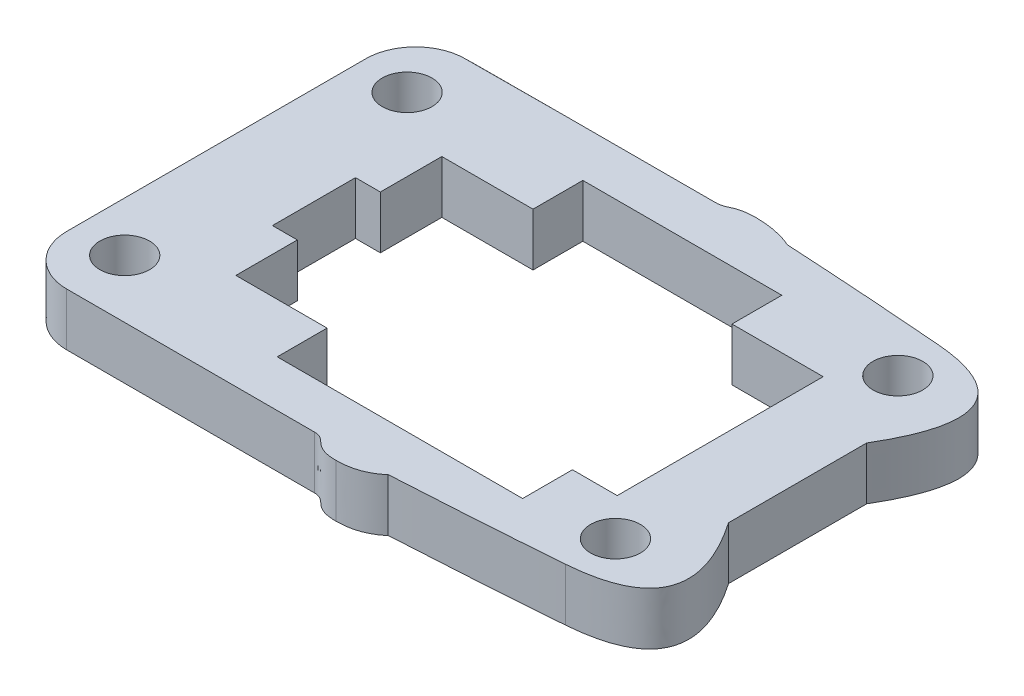
SolidWorks part; units mm, degrees
ref_plane "Front Plane" through (0, 0, 0) normal (0, 0, 1) x (1, 0, 0)
ref_plane "Top Plane" through (0, 0, 0) normal (0, 1, 0) x (1, 0, 0)
ref_plane "Right Plane" through (0, 0, 0) normal (1, 0, 0) x (0, 0, -1)
sketch "Sketch1" plane through (0, 0, 0) normal (0, 1, 0) x (1, 0, 0)
  line L0 (-5.1419, -4.4237) -> (-5.1419, -23.5635) construction
  line L1 (24.4058, -21.4242) -> (-7.2594, -21.4242) construction
  line L25 (-8.1366, -21.9243) -> (-8.1366, -3.9237)
  line L26 (26.9756, -8.8678) -> (26.9756, -17.1873)
  line L27 (-2.247, -15.4242) -> (-0.7496, -15.4242)
  line L28 (-0.7496, -15.4242) -> (-0.7496, -19.1243)
  line L29 (-0.7496, -19.1243) -> (4.7404, -19.1243)
  line L30 (4.7404, -19.1243) -> (4.7404, -22.1242)
  line L31 (4.7404, -22.1242) -> (19.5144, -22.1242)
  line L32 (19.5144, -22.1242) -> (19.5144, -19.1243)
  line L33 (19.5144, -19.1243) -> (22.2095, -19.1243)
  line L34 (22.2095, -19.1243) -> (22.2095, -6.7239)
  line L35 (22.2095, -6.7239) -> (16.7193, -6.7239)
  line L36 (16.7193, -6.7239) -> (16.7193, -3.7237)
  line L37 (16.7193, -3.7237) -> (4.7404, -3.7237)
  line L38 (4.7404, -3.7237) -> (4.7404, -6.7239)
  line L39 (4.7404, -6.7239) -> (-0.7496, -6.7239)
  line L40 (-0.7496, -6.7239) -> (-0.7496, -10.424)
  line L41 (-0.7496, -10.424) -> (-2.247, -10.424)
  line L42 (-2.247, -10.424) -> (-2.247, -15.4242)
  circle A0 centre (-5.1419, -4.4237) radius 1.4974
  circle A1 centre (24.4058, -4.4237) radius 1.4974
  circle A2 centre (-5.1419, -21.4242) radius 1.4974
  circle A3 centre (24.4058, -21.4242) radius 1.4974
  spline S9 degree 3 poles (-8.1366, -3.9237) (-8.1366, -3.1281) (-7.821, -2.365) (-7.2594, -1.8022) knots 1 1 1 1 2 2 2 2
  spline S10 degree 3 poles (-7.2594, -1.8022) (-6.6977, -1.2396) (-5.9362, -0.9236) (-5.1419, -0.9236) knots 2 2 2 2 3 3 3 3
  spline S11 degree 3 poles (-5.1419, -0.9236) (-5.1548, -0.903) (4.1658, -0.8787) (9.8792, -0.888) knots 3 3 3 3 4 4 4 4
  spline S12 degree 3 poles (9.8792, -0.888) (10.625, -0.8893) (10.5642, -0.4517) (11.9066, -0.4517) knots 4 4 4 4 5 5 5 5
  spline S13 degree 3 poles (11.9066, -0.4517) (13.316, -0.4517) (14.2148, -0.9091) (14.2236, -0.9236) knots 5 5 5 5 6 6 6 6
  spline S14 degree 2 poles (14.2236, -0.9236) (19.2567, -1.2064) (23.9716, -1.5887) knots 6 6 6 7 7 7
  spline S15 degree 2 poles (23.9716, -1.5887) (30.9955, -2.1584) (26.9756, -8.8678) knots 7 7 7 8 8 8
  spline S16 degree 2 poles (26.9756, -17.1873) (31.4427, -23.6896) (24.2317, -24.2591) knots 9 9 9 10 10 10
  spline S17 degree 2 poles (24.2317, -24.2591) (19.3908, -24.6415) (14.2236, -24.9242) knots 10 10 10 11 11 11
  spline S18 degree 2 poles (14.2236, -24.9242) (13.2977, -25.7529) (11.9066, -25.7529) knots 11 11 11 12 12 12
  spline S19 degree 3 poles (11.9066, -25.7529) (10.3986, -25.7529) (10.59, -24.9242) (9.7912, -24.9242) knots 12 12 12 12 13 13 13 13
  spline S20 degree 2 poles (9.7912, -24.9242) (4.0745, -24.9242) (-5.1419, -24.9242) knots 13 13 13 14 14 14
  spline S21 degree 3 poles (-5.1419, -24.9242) (-5.9362, -24.9242) (-6.6977, -24.6083) (-7.2594, -24.0457) knots 14 14 14 14 15 15 15 15
  spline S22 degree 3 poles (-7.2594, -24.0457) (-7.821, -23.4831) (-8.1366, -22.7198) (-8.1366, -21.9243) knots 15 15 15 15 16 16 16 16
  point P0 (-5.1419, -4.4237)
  point P1 (24.4058, -4.4237)
  point P2 (24.4058, -21.4242)
  dimension "D1" = 2.9947
extrude "Boss-Extrude1" add sketch "Sketch1" along normal blind 3.175
